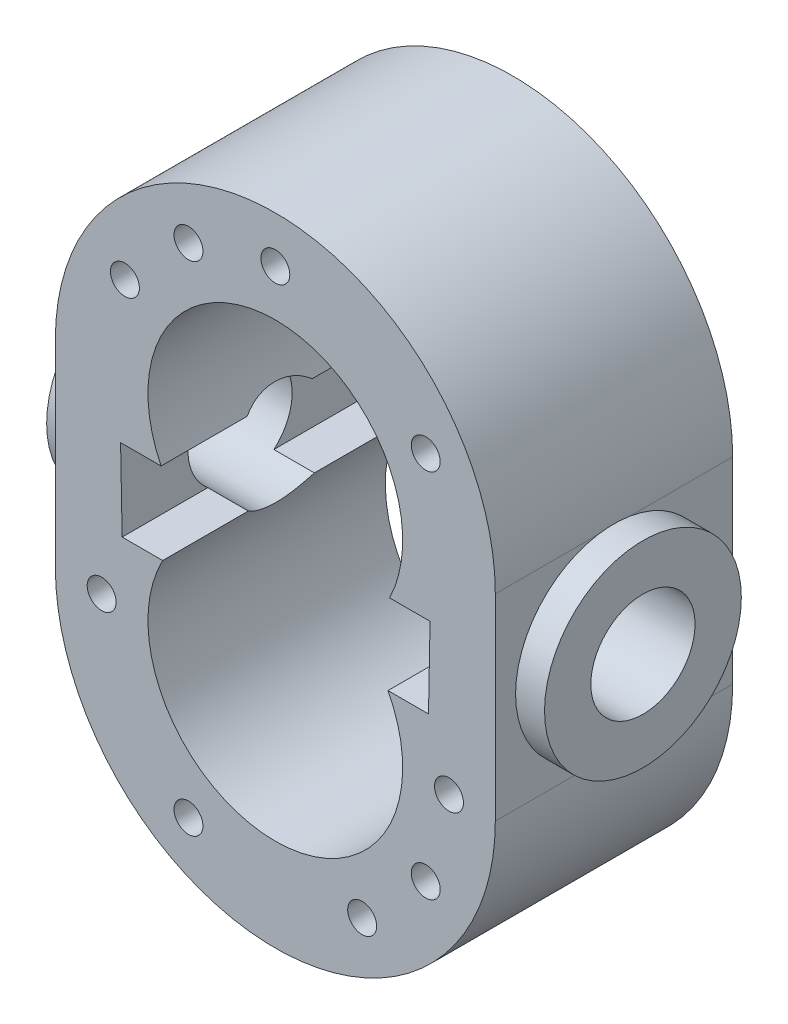
SolidWorks part; units mm, degrees
ref_plane "前视基准面" through (0, 0, 0) normal (0, 0, 1) x (1, 0, 0)
ref_plane "上视基准面" through (0, 0, 0) normal (0, 1, 0) x (1, 0, 0)
ref_plane "右视基准面" through (0, 0, 0) normal (1, 0, 0) x (0, 0, -1)
sketch "草图1" plane through (0, 0, 0) normal (0, 0, 1) x (1, 0, 0)
  line L0 (-73.5526, 0) -> (87.4872, 0) construction
  line L1 (0, 16.7315) -> (0, -17.2685) construction
  line L2 (-38, 16.7315) -> (38, 16.7315) construction
  line L3 (38, 16.7315) -> (38, -17.2685)
  line L4 (-38, 16.7315) -> (-38, -17.2685)
  line L5 (-38, -17.2685) -> (38, -17.2685) construction
  line L6 (-30, 16.7315) -> (-30, -17.2685) construction
  line L7 (30, 16.7315) -> (30, -17.2685) construction
  line L11 (-19.7306, 7) -> (-26.7306, 7)
  line L12 (19.7306, 7) -> (26.7306, 7)
  line L13 (-19.4566, -7) -> (-26.4566, -7)
  line L14 (19.4566, -7) -> (26.4566, -7)
  line L15 (-26.7306, 7) -> (-26.4566, -7)
  line L16 (26.7306, 7) -> (26.4566, -7)
  line L17 (0, 16.7315) -> (25.9808, 31.7315) construction
  line L18 (0, 16.7315) -> (-25.9808, 31.7315) construction
  line L19 (0, -17.2685) -> (-30, -17.2685) construction
  line L20 (0, -17.2685) -> (-15, -43.2493) construction
  line L21 (0, -17.2685) -> (30, -17.2685) construction
  line L22 (0, -17.2685) -> (15, -43.2493) construction
  arc A1 (38, 16.7315) -> (-38, 16.7315) centre (0, 16.7315) ccw
  arc A2 (30, 16.7315) -> (-30, 16.7315) centre (0, 16.7315) ccw construction
  arc A5 (-38, -17.2685) -> (38, -17.2685) centre (0, -17.2685) ccw
  arc A6 (-30, -17.2685) -> (30, -17.2685) centre (0, -17.2685) ccw construction
  arc A8 (-19.4566, -7) -> (19.4566, -7) centre (0, -17.2685) ccw
  arc A10 (19.7306, 7) -> (-19.7306, 7) centre (0, 16.7315) ccw
  dimension "D4" = 7
  dimension "D5" = 7
  dimension "D6" = 44
  dimension "D1" = 34
  dimension "D8" = 7
  dimension "D9" = 7
extrude "凸台-拉伸1" add sketch "草图1" along normal blind 41
sketch "草图3" plane through (-38, 0, 0) normal (-1, 0, 0) x (0, 0, 1)
  line L0 (-10.3324, 0) -> (47.1687, 0) construction
  line L1 (20.5, 23.1001) -> (20.5, -23.1812) construction
  circle A0 centre (20.5, -0.0406) radius 17
  circle A1 centre (20.5, -0.0406) radius 9
extrude "凸台-拉伸3" add sketch "草图3" along normal blind 5 contours A0 | A1
sketch "草图6" plane through (-38, 0, 0) normal (-1, 0, 0) x (0, 0, 1)
  circle A0 centre (20.5, -0.0406) radius 9
extrude "切除-拉伸1" cut sketch "草图6" against normal up to surface (76 mm away) up to face at (38, -0.2685, 20.5)
sketch "草图7" plane through (38, 0, 0) normal (1, 0, 0) x (0, 0, -1)
  circle A0 centre (-20.5, -0.0406) radius 9
  circle A1 centre (-20.5, -0.0406) radius 17
extrude "凸台-拉伸4" add sketch "草图7" along normal blind 5
sketch "草图39" plane through (0, 0, 0) normal (0, 0, -1) x (-1, 0, 0)
  line L0 (0, 54.7315) -> (0, -55.2685) construction
  line L1 (-38, 16.7315) -> (38, 16.7315) construction
  line L2 (-38, -17.2685) -> (38, -17.2685) construction
  line L3 (-30, 16.7315) -> (-30, -17.2685) construction
  line L4 (30, 16.7315) -> (30, -17.2685) construction
  line L5 (-15, 42.7122) -> (0, 16.7315) construction
  line L6 (0, 16.7315) -> (25.9808, 31.7315) construction
  line L7 (-25.9808, 31.7315) -> (0, 16.7315) construction
  line L8 (-28.9778, -25.0331) -> (0, -17.2685) construction
  line L9 (28.9778, -25.0331) -> (0, -17.2685) construction
  line L10 (0, -17.2685) -> (15, -43.2493) construction
  arc A0 (38, 16.7315) -> (-38, 16.7315) centre (0, 16.7315) ccw construction
  arc A1 (-38, -17.2685) -> (38, -17.2685) centre (0, -17.2685) ccw construction
  arc A2 (30, 16.7315) -> (-30, 16.7315) centre (0, 16.7315) ccw construction
  arc A3 (-30, -17.2685) -> (30, -17.2685) centre (0, -17.2685) ccw construction
  circle A4 centre (0, 47.0278) radius 2.5
  circle A5 centre (0, -47.2685) radius 2.5
  circle A6 centre (25.9808, 31.7315) radius 2.5
  circle A7 centre (-25.9808, 31.7315) radius 2.5
  circle A8 centre (-28.9778, -25.0331) radius 2.5
  circle A10 centre (-15, 42.7122) radius 2.5
  circle A11 centre (28.9778, -25.0331) radius 2.5
  circle A12 centre (15, -43.2493) radius 2.5
  dimension "D1" = 30
  dimension "D2" = 60
  dimension "D3" = 60
  dimension "D4" = 15
  dimension "D5" = 60
  dimension "D6" = 15
hole_wizard "M6 螺纹孔1" positions "3D草图12" profile "草图40" tap size "M6" standard "GB"
sketch3d "3D草图12"
  point P0 (0, 47.0278, 0)
  point P3 (25.9808, 31.7315, 0)
  point P6 (28.9778, -25.0331, 0)
  point P9 (0, -47.2685, 0)
  point P12 (-28.9778, -25.0331, 0)
  point P15 (-25.9808, 31.7315, 0)
sketch "草图40" plane through (0, 47.0278, 0) normal (1, 0, 0) x (0, 1, 0)
  line L0 (0, 0) -> (0, 18.5022)
  line L1 (0, 18.5022) -> (2.5, 17)
  line L2 (2.5, 17) -> (2.5, 0)
  line L5 (2.5, 0) -> (0, 0)
  line L10 (0, 18.5022) -> (-2.5, 17) construction
  line L11 (0, -6.35) -> (0, 107.95) construction
  dimension "螺纹孔钻头直径" = 5
  dimension "螺纹孔钻头深度" = 17
  dimension "导头角度" = 118
cosmetic thread "孔螺蚊线1" parameters "D1"=12, "D2"=6
cosmetic thread "孔螺蚊线2" parameters "D1"=12, "D2"=6
cosmetic thread "孔螺蚊线3" parameters "D1"=12, "D2"=6
cosmetic thread "孔螺蚊线4" parameters "D1"=12, "D2"=6
cosmetic thread "孔螺蚊线5" parameters "D1"=12, "D2"=6
cosmetic thread "孔螺蚊线6" parameters "D1"=12, "D2"=6
hole_wizard "Ø5.0 (5) 直径孔1" positions "3D草图13" profile "草图41" hole size "Ø5.0" standard "GB"
sketch3d "3D草图13"
  point P0 (15, 42.7122, 0)
  point P3 (-15, -43.2493, 0)
sketch "草图41" plane through (15, 42.7122, 0) normal (1, 0, 0) x (0, 1, 0)
  line L0 (0, 0) -> (0, 6.5022)
  line L1 (0, 6.5022) -> (2.5, 5)
  line L2 (2.5, 5) -> (2.5, 0)
  line L5 (2.5, 0) -> (0, 0)
  line L10 (0, 6.5022) -> (-2.5, 5) construction
  line L11 (0, -6.35) -> (0, 107.95) construction
  dimension "孔直径" = 5
  dimension "孔深度" = 5
  dimension "导头角度" = 118
sketch "草图42" plane through (0, 0, 41) normal (0, 0, 1) x (1, 0, 0)
  line L0 (-15, 42.7122) -> (0, 16.7315) construction
  line L1 (0, 16.7315) -> (25.9808, 31.7315) construction
  line L2 (-25.9808, 31.7315) -> (0, 16.7315) construction
  line L3 (-15, -43.2493) -> (0, -17.2685) construction
  line L4 (0, -17.2685) -> (15, -43.2493) construction
  line L5 (0, -17.2685) -> (25.9808, -32.2685) construction
  line L6 (0, 54.7315) -> (0, -55.2685) construction
  circle A0 centre (0, 16.7315) radius 30 construction
  circle A1 centre (0, -17.2685) radius 30 construction
  circle A2 centre (0, 46.7315) radius 2.5
  circle A3 centre (-25.9808, 31.7315) radius 2.5
  circle A4 centre (25.9808, 31.7315) radius 2.5
  circle A5 centre (-15, 42.7122) radius 2.5
  circle A6 centre (-15, -43.2493) radius 2.5
  circle A7 centre (15, -43.2493) radius 2.5
  circle A8 centre (30, -17.2685) radius 2.5
  circle A9 centre (-30, -17.2685) radius 2.5
  circle A10 centre (25.9808, -32.2685) radius 2.5
  arc A11 (38, 16.7315) -> (-38, 16.7315) centre (0, 16.7315) ccw construction
  arc A12 (-38, -17.2685) -> (38, -17.2685) centre (0, -17.2685) ccw construction
  dimension "D1" = 30
  dimension "D2" = 60
  dimension "D3" = 60
  dimension "D4" = 30
  dimension "D5" = 60
  dimension "D6" = 30
hole_wizard "M6 螺纹孔2" positions "3D草图14" profile "草图43" tap size "M6" standard "GB"
sketch3d "3D草图14"
  point P0 (0, 46.7315, 41)
  point P3 (-25.9808, 31.7315, 41)
  point P6 (25.9808, 31.7315, 41)
  point P9 (30, -17.2685, 41)
  point P12 (-30, -17.2685, 41)
  point P15 (-15, -43.2493, 41)
  point P18 (15, -43.2493, 41)
sketch "草图43" plane through (0, 46.7315, 41) normal (1, 0, 0) x (0, -1, 0)
  line L0 (0, 0) -> (0, 18.5022)
  line L1 (0, 18.5022) -> (2.5, 17)
  line L2 (2.5, 17) -> (2.5, 0)
  line L5 (2.5, 0) -> (0, 0)
  line L10 (0, 18.5022) -> (-2.5, 17) construction
  line L11 (0, -6.35) -> (0, 107.95) construction
  dimension "螺纹孔钻头直径" = 5
  dimension "螺纹孔钻头深度" = 17
  dimension "导头角度" = 118
cosmetic thread "孔螺蚊线7" parameters "D1"=12, "D2"=6
cosmetic thread "孔螺蚊线8" parameters "D1"=12, "D2"=6
cosmetic thread "孔螺蚊线9" parameters "D1"=12, "D2"=6
cosmetic thread "孔螺蚊线10" parameters "D1"=12, "D2"=6
cosmetic thread "孔螺蚊线11" parameters "D1"=12, "D2"=6
cosmetic thread "孔螺蚊线12" parameters "D1"=12, "D2"=6
cosmetic thread "孔螺蚊线13" parameters "D1"=12, "D2"=6
hole_wizard "Ø5.0 (5) 直径孔2" positions "3D草图15" profile "草图44" hole size "Ø5.0" standard "GB"
sketch3d "3D草图15"
  point P0 (-15, 42.7122, 41)
  point P3 (25.9808, -32.2685, 41)
sketch "草图44" plane through (-15, 42.7122, 41) normal (1, 0, 0) x (0, -1, 0)
  line L0 (0, 0) -> (0, 18.5022)
  line L1 (0, 18.5022) -> (2.5, 17)
  line L2 (2.5, 17) -> (2.5, 0)
  line L5 (2.5, 0) -> (0, 0)
  line L10 (0, 18.5022) -> (-2.5, 17) construction
  line L11 (0, -6.35) -> (0, 107.95) construction
  dimension "孔直径" = 5
  dimension "孔深度" = 17
  dimension "导头角度" = 118
